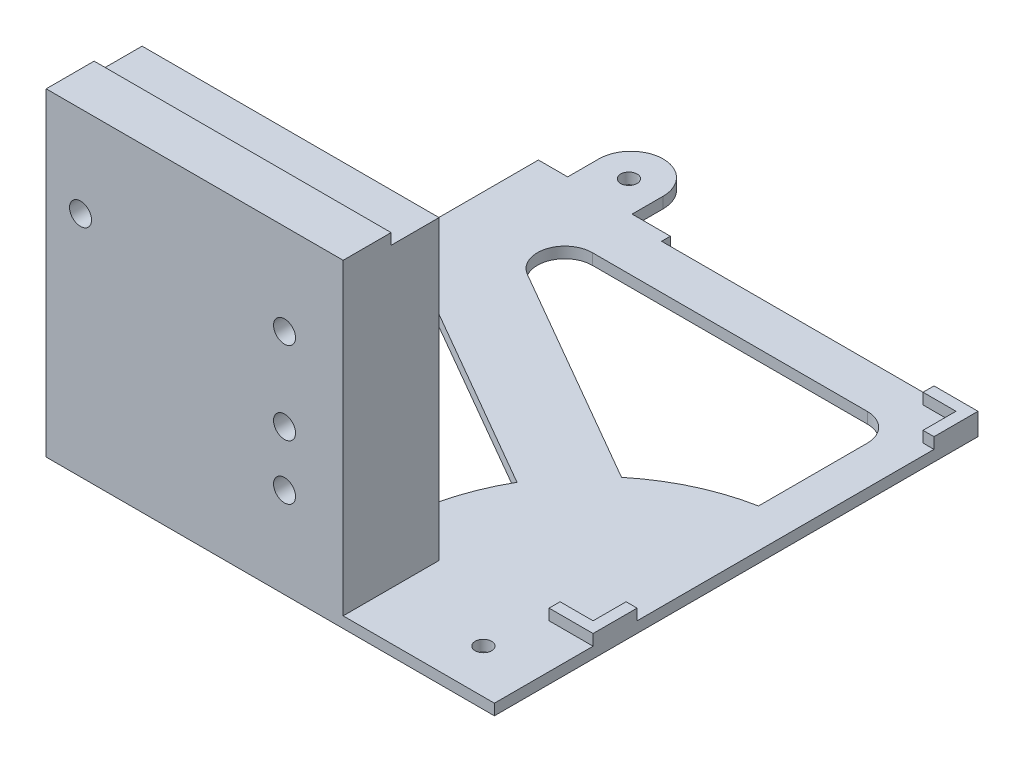
SolidWorks part; units mm, degrees
ref_plane "前视基准面" through (0, 0, 0) normal (0, 0, 1) x (1, 0, 0)
ref_plane "上视基准面" through (0, 0, 0) normal (0, 1, 0) x (1, 0, 0)
ref_plane "右视基准面" through (0, 0, 0) normal (1, 0, 0) x (0, 0, -1)
sketch "草图1" plane through (0, 62.5, 0) normal (0, 1, 0) x (1, 0, 0)
  line L1 (-69.1412, -223.5127) -> (-69.1412, 38) construction
  line L2 (12.4028, -4.8112) -> (-45.1412, -4.8112)
  line L3 (12.4028, -4.8112) -> (12.4028, -92.7563)
  line L4 (12.4028, -92.7563) -> (-69.1412, -92.7563)
  line L5 (-69.1412, -4.8112) -> (-69.1412, -92.7563)
  line L6 (-45.1412, 38) -> (-45.1412, 50.7319) construction
  line L8 (-69.1412, -4.8112) -> (-69.1412, 44.366)
  line L9 (-69.1412, 44.366) -> (-45.1412, 44.366)
  line L10 (-45.1412, -4.8112) -> (-45.1412, 44.366)
extrude "凸台-拉伸1" add sketch "草图1" along normal blind 2
sketch "草图2" plane through (0, 64.5, 0) normal (0, 1, 0) x (1, 0, 0)
  line L9 (12.4028, -4.8112) -> (4.4028, -4.8112)
  line L10 (12.4028, -4.8112) -> (-45.1412, -4.8112) construction
  line L11 (4.4028, -4.8112) -> (4.4028, -6.8112)
  line L12 (4.4028, -6.8112) -> (10.4028, -6.8112)
  line L13 (10.4028, -6.8112) -> (10.4028, -12.8112)
  line L14 (10.4028, -12.8112) -> (12.4028, -12.8112)
  line L15 (12.4028, -92.7563) -> (12.4028, -4.8112) construction
  line L16 (12.4028, -12.8112) -> (12.4028, -4.8112)
  line L17 (12.4028, -66.8112) -> (10.4028, -66.8112)
  line L18 (10.4028, -66.8112) -> (10.4028, -72.8112)
  line L19 (10.4028, -72.8112) -> (4.4028, -72.8112)
  line L20 (4.4028, -72.8112) -> (4.4028, -74.8112)
  line L21 (4.4028, -74.8112) -> (12.4028, -74.8112)
  line L22 (12.4028, -74.8112) -> (12.4028, -66.8112)
  line L23 (12.4028, -74.8112) -> (-77.4259, -74.8112) construction
  line L24 (-69.1103, -74.8112) -> (-69.1103, -66.8112)
  line L25 (-69.1103, -66.8112) -> (-67.1103, -66.8112)
  line L26 (-67.1103, -66.8112) -> (-67.1103, -72.8112)
  line L27 (-67.1103, -72.8112) -> (-61.1103, -72.8112)
  line L28 (-61.1103, -72.8112) -> (-61.1103, -74.8112)
  line L29 (-61.1103, -74.8112) -> (-69.1103, -74.8112)
  dimension "D1" = 70
extrude "凸台-拉伸2" add sketch "草图2" along normal blind 2
sketch "草图3" plane through (0, 64.5, 0) normal (0, 1, 0) x (1, 0, 0)
  line L0 (-69.1412, -92.7563) -> (12.4028, -92.7563) construction
  line L1 (-69.1103, -75.3112) -> (-15.1027, -75.3112)
  line L2 (-69.1103, -75.3112) -> (-69.1103, -92.7563)
  line L3 (-69.1103, -92.7563) -> (-15.1027, -92.7563)
  line L4 (-15.1027, -75.3112) -> (-15.1027, -92.7563)
  line L5 (-69.1103, -74.8112) -> (-61.1103, -74.8112) construction
  dimension "D1" = 0.5
extrude "凸台-拉伸4" add sketch "草图3" along normal blind 54
sketch "草图4" plane through (0, 118.5, 0) normal (0, 1, 0) x (1, 0, 0)
  line L0 (-69.1103, -75.3112) -> (-69.1103, -92.7563) construction
  line L1 (-69.1103, -84.0338) -> (-15.1027, -84.0338)
  line L2 (-69.1103, -84.0338) -> (-69.1103, -92.7563)
  line L3 (-69.1103, -92.7563) -> (-15.1027, -92.7563)
  line L4 (-15.1027, -84.0338) -> (-15.1027, -92.7563)
extrude "凸台-拉伸5" add sketch "草图4" along normal blind 2
sketch "草图5" plane through (0, 64.5, 0) normal (0, 1, 0) x (1, 0, 0)
  line L0 (-45.1412, -4.8112) -> (-45.1412, 44.366) construction
  line L1 (-69.1412, 44.366) -> (-45.1412, 44.366)
  line L2 (-69.1412, 44.366) -> (-69.1412, 12.9396)
  line L4 (-45.1412, 44.366) -> (-45.1412, 12.9396)
  line L5 (-69.1412, 12.9396) -> (-69.1412, -3.2104)
  line L6 (-69.1412, 44.366) -> (-69.1412, -92.7563) construction
  line L7 (-69.1412, -3.2104) -> (-63.8206, -3.2104)
  line L8 (-63.8206, -3.2104) -> (-63.8206, 2.4421)
  line L9 (-52.0999, 2.4421) -> (-52.0999, -3.2104)
  line L10 (-52.0999, -3.2104) -> (-45.1412, -3.2104)
  line L11 (-45.1412, -3.2104) -> (-45.1412, 12.9396)
  arc A0 (-63.8206, 2.4421) -> (-52.0999, 2.4421) centre (-57.9603, 2.4421) cw
extrude "切除-拉伸1" cut sketch "草图5" against normal blind 2
sketch "草图6" plane through (0, 64.5, 0) normal (0, 1, 0) x (1, 0, 0)
  line L0 (-57.9603, 13.645) -> (-57.9603, -2.3514) construction
  line L1 (-63.8206, -3.2104) -> (-63.8206, 2.4421) construction
  line L2 (-52.0999, 2.4421) -> (-52.0999, -3.2104) construction
  line L3 (-45.1412, 2.0653) -> (-69.1412, 2.0653) construction
  circle A0 centre (-57.9603, 2.0653) radius 1.5
  dimension "D1" = 3
extrude "切除-拉伸2" cut sketch "草图6" against normal blind 2
sketch "草图7" plane through (0, 64.5, 0) normal (0, 1, 0) x (1, 0, 0)
  line L0 (-15.1027, -92.7563) -> (12.4028, -92.7563) construction
  line L2 (12.4028, -92.7563) -> (12.4028, -74.8112) construction
  circle A0 centre (2.4028, -84.7563) radius 1.5
  dimension "D1" = 8
  dimension "D3" = 3
  dimension "D2" = 10
extrude "切除-拉伸3" cut sketch "草图7" against normal blind 2
sketch "草图8" plane through (0, 0, 92.7563) normal (0, 0, 1) x (1, 0, 0)
  circle A0 centre (-62.8629, 103.9526) radius 2
  circle A1 centre (-25.7629, 103.9526) radius 2
extrude "切除-拉伸4" cut sketch "草图8" against normal blind 10
sketch "草图9" plane through (0, 0, 92.7563) normal (0, 0, 1) x (1, 0, 0)
  line L0 (-76.9111, 78.9526) -> (-17.3673, 78.9526) construction
  line L2 (-62.8629, 103.9526) -> (-62.8629, 67.4528) construction
  line L3 (-25.7629, 103.9526) -> (-25.7629, 67.4528) construction
  line L4 (-25.7629, 103.9526) -> (-17.3673, 103.9526) construction
  circle A1 centre (-25.7629, 78.9526) radius 2
  circle A2 centre (-25.7629, 88.9526) radius 2
  dimension "D2" = 4
  dimension "D3" = 4
  dimension "D1" = 25
  dimension "D4" = 10
extrude "切除-拉伸5" cut sketch "草图9" against normal blind 10
sketch "草图10" plane through (0, 64.5, 0) normal (0, 1, 0) x (1, 0, 0)
  line L0 (-49.641, -12.8952) -> (0.359, -12.8952)
  line L1 (5.359, -17.8952) -> (5.359, -37.6832)
  line L2 (-11.6065, -45.628) -> (-52.141, -22.2253)
  line L3 (-20.3246, -55.9161) -> (-56.4505, -35.0588)
  line L4 (-60.4445, -37.3647) -> (-60.4445, -67.0768)
  line L5 (-58.9416, -68.5797) -> (-24.8702, -68.5797)
  arc A0 (0.359, -12.8952) -> (5.359, -17.8952) centre (0.359, -17.8952) cw
  arc A2 (-52.141, -22.2253) -> (-49.641, -12.8952) centre (-49.641, -17.8952) cw
  arc A4 (5.359, -37.6832) -> (-11.6065, -45.628) centre (12.4028, -74.8112) ccw
  arc A5 (5.359, -37.6832) -> (-11.6065, -45.628) centre (12.4028, -74.8112) ccw construction
  arc A6 (-56.4505, -35.0588) -> (-60.4445, -37.3647) centre (-57.7818, -37.3647) ccw
  arc A7 (-60.4445, -67.0768) -> (-58.9416, -68.5797) centre (-58.9416, -67.0768) ccw
  arc A8 (-20.3246, -55.9161) -> (-24.8702, -68.5797) centre (12.4028, -74.8112) ccw
  arc A9 (-20.3246, -55.9161) -> (-24.8702, -68.5797) centre (12.4028, -74.8112) ccw construction
  dimension "D1" = 30
  dimension "D2" = 5
  dimension "D3" = 5
  dimension "D4" = 50
extrude "切除-拉伸6" cut sketch "草图10" against normal blind 10
